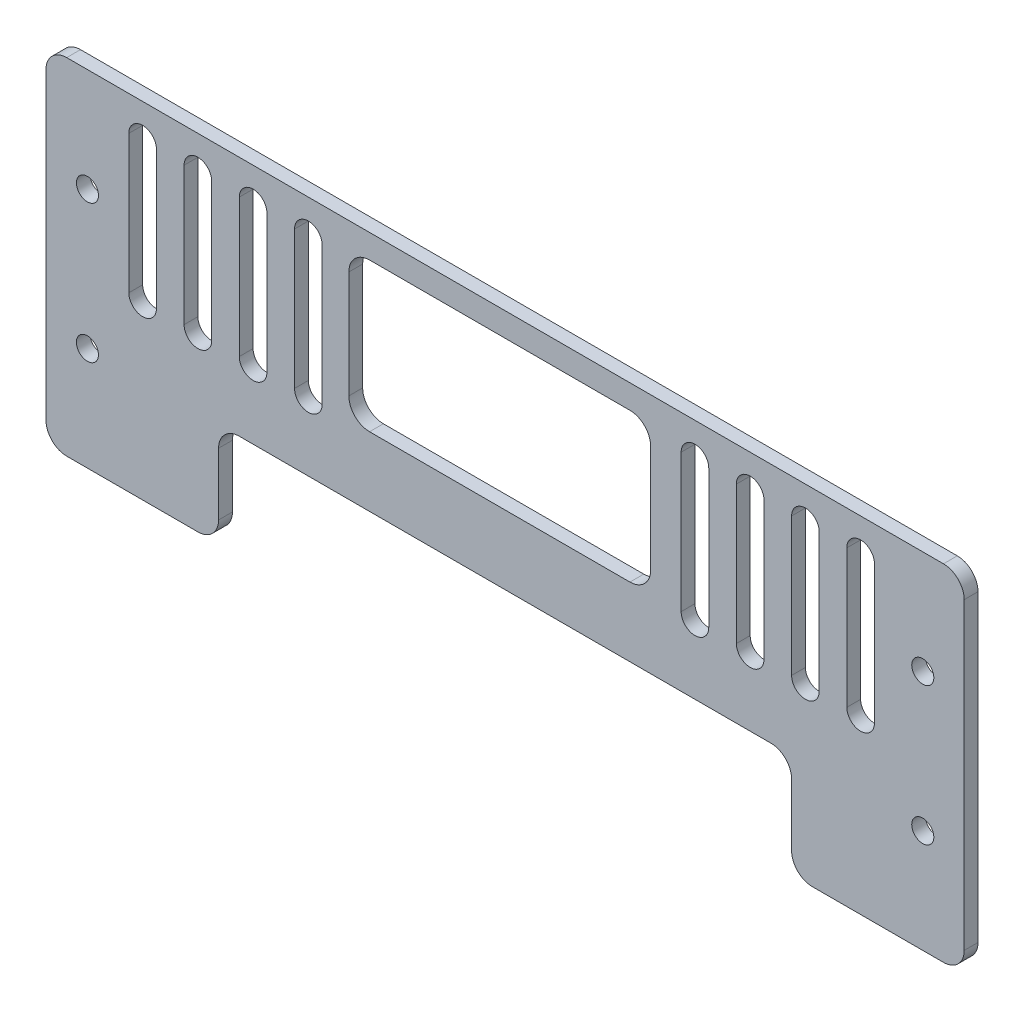
SolidWorks part; units mm, degrees
ref_plane "前视基准面" through (0, 0, 0) normal (0, 0, 1) x (1, 0, 0)
ref_plane "上视基准面" through (0, 0, 0) normal (0, 1, 0) x (1, 0, 0)
ref_plane "右视基准面" through (0, 0, 0) normal (1, 0, 0) x (0, 0, -1)
other "Configuration Table"
sketch "草图1" plane through (0, 0, 0) normal (0, 0, 1) x (1, 0, 0)
  line L1 (66.5, -25) -> (-66.5, -25)
  line L2 (66.5, -25) -> (66.5, 25)
  line L3 (66.5, 25) -> (-66.5, 25)
  line L4 (-66.5, -25) -> (-66.5, 25)
  line L5 (66.5, -25) -> (-66.5, 25) construction
  line L6 (66.5, 25) -> (-66.5, -25) construction
  point P0 (0, 0)
  dimension "D1" = 133
  dimension "D2" = 50
extrude "凸台-拉伸1" add sketch "草图1" along normal blind 2
fillet "圆角1" radius 3 4 edges at (66.5, 25, 1) (66.5, -25, 1) (-66.5, -25, 1) (-66.5, 25, 1)
sketch "草图2" plane through (0, 0, 2) normal (0, 0, 1) x (1, 0, 0)
  line L0 (0, 25) -> (0, -25) construction
  line L1 (63.5, 25) -> (-63.5, 25) construction
  line L2 (-63.5, -25) -> (63.5, -25) construction
  line L3 (-60.5, 25) -> (-60.5, -25) construction
  line L5 (-66.5, 22) -> (-66.5, -22) construction
  line L6 (60.5, 25) -> (60.5, -25) construction
  circle A0 centre (-60.5, 10) radius 1.6
  circle A1 centre (-60.5, -10) radius 1.6
  circle A2 centre (60.5, -10) radius 1.6
  circle A3 centre (60.5, 10) radius 1.6
  dimension "D2" = 3.2
  dimension "D3" = 20
  dimension "D4" = 15
  dimension "D1" = 6
extrude "切除-拉伸1" cut sketch "草图2" against normal blind 3
sketch "草图3" plane through (0, 0, 2) normal (0, 0, 1) x (1, 0, 0)
  line L0 (-52.5, 20) -> (-52.5, 0) construction
  line L1 (-50.5, 20) -> (-50.5, 0)
  line L2 (-54.5, 20) -> (-54.5, 0)
  line L3 (-66.5, 22) -> (-66.5, -22) construction
  line L4 (-52.5, 0) -> (0, 0) construction
  line L5 (-46.5, 20) -> (-46.5, 0)
  line L6 (-42.5, 20) -> (-42.5, 0)
  line L7 (-44.5, 20) -> (-44.5, 0) construction
  line L8 (-38.5, 20) -> (-38.5, 0)
  line L9 (-34.5, 20) -> (-34.5, 0)
  line L10 (-36.5, 20) -> (-36.5, 0) construction
  line L11 (-30.5, 20) -> (-30.5, 0)
  line L12 (-26.5, 20) -> (-26.5, 0)
  line L13 (-28.5, 20) -> (-28.5, 0) construction
  line L31 (-22.6315, 21.5422) -> (21.0834, 21.5422)
  line L32 (25.5, 20) -> (25.5, 0)
  line L33 (29.5, 20) -> (29.5, 0)
  line L34 (27.5, 20) -> (27.5, 0) construction
  line L35 (33.5, 20) -> (33.5, 0)
  line L36 (37.5, 20) -> (37.5, 0)
  line L37 (35.5, 20) -> (35.5, 0) construction
  line L38 (41.5, 20) -> (41.5, 0)
  line L39 (45.5, 20) -> (45.5, 0)
  line L40 (43.5, 20) -> (43.5, 0) construction
  line L41 (49.5, 20) -> (49.5, 0)
  line L42 (53.5, 20) -> (53.5, 0)
  line L43 (51.5, 20) -> (51.5, 0) construction
  line L44 (63.5, 25) -> (-63.5, 25) construction
  line L46 (-2.5, 20) -> (-2.5, 0) [skipped]
  line L47 (-6.5, 20) -> (-6.5, 0) [skipped]
  line L48 (5.5, 20) -> (5.5, 0) [skipped]
  line L49 (1.5, 20) -> (1.5, 0) [skipped]
  line L50 (13.5, 20) -> (13.5, 0) [skipped]
  line L51 (9.5, 20) -> (9.5, 0) [skipped]
  line L52 (21.5, 20) -> (21.5, 0) [skipped]
  line L53 (17.5, 20) -> (17.5, 0) [skipped]
  line L54 (-10.5, 20) -> (-10.5, 0) [skipped]
  line L55 (-14.5, 20) -> (-14.5, 0) [skipped]
  line L56 (-18.5, 20) -> (-18.5, 0) [skipped]
  line L57 (-22.5, 20) -> (-22.5, 0) [skipped]
  line L58 (-22.6315, 21.5422) -> (-22.6315, 0)
  line L59 (-22.6315, 0) -> (21.0834, 0)
  line L60 (21.0834, 21.5422) -> (21.0834, 0)
  arc A0 (-50.5, 20) -> (-54.5, 20) centre (-52.5, 20) ccw
  arc A1 (-54.5, 0) -> (-50.5, 0) centre (-52.5, 0) ccw
  arc A2 (-42.5, 20) -> (-46.5, 20) centre (-44.5, 20) ccw
  arc A3 (-46.5, 0) -> (-42.5, 0) centre (-44.5, 0) ccw
  arc A4 (-34.5, 20) -> (-38.5, 20) centre (-36.5, 20) ccw
  arc A5 (-38.5, 0) -> (-34.5, 0) centre (-36.5, 0) ccw
  arc A6 (-26.5, 20) -> (-30.5, 20) centre (-28.5, 20) ccw
  arc A7 (-30.5, 0) -> (-26.5, 0) centre (-28.5, 0) ccw
  arc A20 (29.5, 20) -> (25.5, 20) centre (27.5, 20) ccw
  arc A21 (25.5, 0) -> (29.5, 0) centre (27.5, 0) ccw
  arc A22 (37.5, 20) -> (33.5, 20) centre (35.5, 20) ccw
  arc A23 (33.5, 0) -> (37.5, 0) centre (35.5, 0) ccw
  arc A24 (45.5, 20) -> (41.5, 20) centre (43.5, 20) ccw
  arc A25 (41.5, 0) -> (45.5, 0) centre (43.5, 0) ccw
  arc A26 (53.5, 20) -> (49.5, 20) centre (51.5, 20) ccw
  arc A27 (49.5, 0) -> (53.5, 0) centre (51.5, 0) ccw
  arc A28 (-2.5, 20) -> (-6.5, 20) centre (-4.5, 20) ccw [skipped]
  arc A29 (-6.5, 0) -> (-2.5, 0) centre (-4.5, 0) ccw [skipped]
  arc A30 (5.5, 20) -> (1.5, 20) centre (3.5, 20) ccw [skipped]
  arc A31 (1.5, 0) -> (5.5, 0) centre (3.5, 0) ccw [skipped]
  arc A32 (13.5, 20) -> (9.5, 20) centre (11.5, 20) ccw [skipped]
  arc A33 (9.5, 0) -> (13.5, 0) centre (11.5, 0) ccw [skipped]
  arc A34 (21.5, 20) -> (17.5, 20) centre (19.5, 20) ccw [skipped]
  arc A35 (17.5, 0) -> (21.5, 0) centre (19.5, 0) ccw [skipped]
  arc A36 (-10.5, 20) -> (-14.5, 20) centre (-12.5, 20) ccw [skipped]
  arc A37 (-14.5, 0) -> (-10.5, 0) centre (-12.5, 0) ccw [skipped]
  arc A38 (-18.5, 20) -> (-22.5, 20) centre (-20.5, 20) ccw [skipped]
  arc A39 (-22.5, 0) -> (-18.5, 0) centre (-20.5, 0) ccw [skipped]
  point P2 (-52.5, 10)
  point P15 (-44.5, 10)
  point P22 (-36.5, 10)
  point P29 (-28.5, 10)
  point P78 (27.5, 10)
  point P85 (35.5, 10)
  point P92 (43.5, 10)
  point P99 (51.5, 10)
  dimension "D1" = 2
  dimension "D5" = 5
  dimension "D2" = 20
  dimension "D3" = 12
  dimension "D4" = 14
extrude "切除-拉伸2" cut sketch "草图3" against normal blind 10
sketch "草图4" plane through (0, 0, 2) normal (0, 0, 1) x (1, 0, 0)
  line L1 (-41.5, -10) -> (41.5, -10)
  line L2 (-41.5, -10) -> (-41.5, -25)
  line L3 (-41.5, -25) -> (41.5, -25)
  line L4 (41.5, -10) -> (41.5, -25)
  line L5 (-66.5, 22) -> (-66.5, -22) construction
  line L6 (66.5, -22) -> (66.5, 22) construction
  line L8 (-63.5, -25) -> (63.5, -25) construction
  dimension "D2" = 25
  dimension "D3" = 25
  dimension "D4" = 15
extrude "切除-拉伸3" cut sketch "草图4" against normal blind 10
fillet "圆角3" radius 3 4 edges at (41.5, -10, 1) (41.5, -25, 1) (-41.5, -10, 1) (-41.5, -25, 1)
fillet "圆角4" radius 3 4 edges at (21.0834, 21.5422, 1) (21.0834, 0, 1) (-22.6315, 0, 1) (-22.6315, 21.5422, 1)
